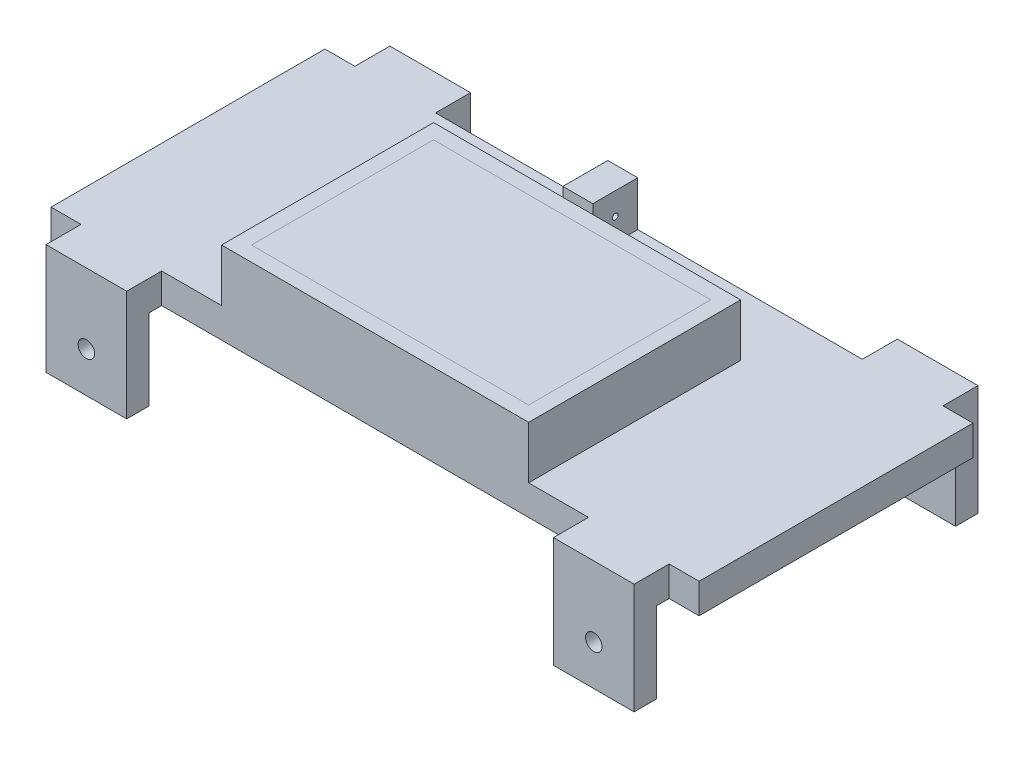
SolidWorks part; units mm, degrees
ref_plane "Front Plane" through (0, 0, 0) normal (0, 0, 1) x (1, 0, 0)
ref_plane "Top Plane" through (0, 0, 0) normal (0, 1, 0) x (1, 0, 0)
ref_plane "Right Plane" through (0, 0, 0) normal (1, 0, 0) x (0, 0, -1)
sketch "Sketch1" plane through (0, 0, 0) normal (1, 0, 0) x (0, 0, -1)
  line L0 (18.2875, 20.8275) -> (-18.2875, 20.8275)
  line L1 (14.2875, -16.8275) -> (-14.2875, -16.8275)
  line L2 (14.2875, -16.8275) -> (14.2875, 16.8275)
  line L3 (14.2875, 16.8275) -> (-14.2875, 16.8275)
  line L4 (-14.2875, -16.8275) -> (-14.2875, 16.8275)
  line L5 (14.2875, -16.8275) -> (-14.2875, 16.8275) construction
  line L6 (14.2875, 16.8275) -> (-14.2875, -16.8275) construction
  line L7 (-18.2875, -20.8275) -> (-18.2875, 20.8275)
  line L8 (18.2875, -20.8275) -> (-18.2875, -20.8275)
  line L9 (18.2875, -20.8275) -> (18.2875, 20.8275)
  point P0 (0, 0)
  dimension "D1" = 28.575
  dimension "D2" = 33.655
  dimension "D3" = 4
extrude "Boss-Extrude1" add sketch "Sketch1" along normal mid plane 82.55
sketch "Sketch2" plane through (-41.275, 0, 0) normal (-1, 0, 0) x (0, 0, 1)
  line L4 (-18.2875, 20.8275) -> (-18.2875, -20.8275)
  line L5 (-18.2875, -20.8275) -> (18.2875, -20.8275)
  line L6 (18.2875, -20.8275) -> (18.2875, 20.8275)
  line L7 (18.2875, 20.8275) -> (-18.2875, 20.8275)
  line L8 (-18.2875, 20.8275) -> (-18.2875, -20.8275)
  line L9 (-18.2875, -20.8275) -> (18.2875, -20.8275)
  line L10 (18.2875, -20.8275) -> (18.2875, 20.8275)
  line L11 (18.2875, 20.8275) -> (-18.2875, 20.8275)
  dimension "D1" = 0
extrude "Boss-Extrude2" add sketch "Sketch2" along normal blind 2
mirror "Mirror1" about plane through (0, 0, 0) normal (1, 0, 0) of "Boss-Extrude2"
sketch "Sketch4" plane through (0, -20.8275, 0) normal (0, -1, 0) x (1, 0, 0)
  line L4 (43.275, 18.2875) -> (-43.275, 18.2875)
  line L5 (-43.275, 18.2875) -> (-43.275, -18.2875)
  line L6 (-43.275, -18.2875) -> (43.275, -18.2875)
  line L7 (43.275, -18.2875) -> (43.275, 18.2875)
  line L8 (43.275, 18.2875) -> (-43.275, 18.2875)
  line L9 (-43.275, 18.2875) -> (-43.275, -18.2875)
  line L10 (-43.275, -18.2875) -> (43.275, -18.2875)
  line L11 (43.275, -18.2875) -> (43.275, 18.2875)
  dimension "D1" = 0
extrude "Cut-Extrude2" cut sketch "Sketch4" against normal blind 37.655
sketch "Sketch5" plane through (0, 0, -18.2875) normal (0, 0, -1) x (-1, 0, 0)
  line L1 (-28.4998, 6.0523) -> (-39.275, 6.0523) construction
  line L2 (-28.4998, 6.0523) -> (-28.4998, 16.8275) construction
  line L3 (-28.4998, 16.8275) -> (-39.275, 16.8275) construction
  line L4 (-39.275, 6.0523) -> (-39.275, 16.8275) construction
  line L5 (-28.4998, 6.0523) -> (-39.275, 16.8275) construction
  line L6 (-28.4998, 16.8275) -> (-39.275, 6.0523) construction
  line L7 (43.275, 16.8275) -> (-43.275, 16.8275) construction
  line L8 (-43.275, 20.8275) -> (-43.275, 16.8275) construction
  line L9 (-39.275, 16.8275) -> (-28.4998, 16.8275)
  line L10 (-31.4998, 9.0523) -> (-36.275, 9.0523) construction
  line L11 (-31.4998, 9.0523) -> (-31.4998, 13.8275) construction
  line L12 (-31.4998, 13.8275) -> (-36.275, 13.8275) construction
  line L13 (-36.275, 9.0523) -> (-36.275, 13.8275) construction
  line L14 (-31.4998, 9.0523) -> (-36.275, 13.8275) construction
  line L15 (-31.4998, 13.8275) -> (-36.275, 9.0523) construction
  line L16 (-28.4998, 16.8275) -> (-28.4998, 20.8275)
  line L17 (-43.275, 20.8275) -> (43.275, 20.8275) construction
  line L18 (-28.4998, 20.8275) -> (-39.275, 20.8275)
  line L19 (-39.275, 20.8275) -> (-39.275, 16.8275)
  point P0 (-33.8874, 11.4399)
  point P9 (-33.8874, 11.4399)
  dimension "D1" = 4
  dimension "D2" = 3
  dimension "D3" = 4.7752
extrude "Boss-Extrude3" add sketch "Sketch5" along normal blind 1.6764
sketch "Sketch6" plane through (0, 0, -19.9639) normal (0, 0, -1) x (-1, 0, 0)
  line L0 (-33.8874, 16.8275) -> (-33.8874, 6.0523) construction
  line L1 (-28.4998, 6.0523) -> (-39.275, 6.0523)
  line L2 (-28.4998, 6.0523) -> (-28.4998, 20.8275)
  line L3 (-28.4998, 20.8275) -> (-39.275, 20.8275)
  line L4 (-39.275, 6.0523) -> (-39.275, 20.8275)
  line L5 (-28.4998, 6.0523) -> (-39.275, 20.8275) construction
  line L6 (-28.4998, 20.8275) -> (-39.275, 6.0523) construction
  line L7 (-39.275, 16.8275) -> (-28.4998, 16.8275) construction
  circle A0 centre (-33.8874, 11.4399) radius 1.1
  point P0 (-33.8874, 13.4399)
  dimension "D1" = 2.2
extrude "Boss-Extrude4" add sketch "Sketch6" along normal blind 3
mirror "Mirror2" about plane through (0, 0, 0) normal (1, 0, 0) of "Boss-Extrude4", "Boss-Extrude3"
mirror "Mirror3" about plane through (0, 0, 0) normal (0, 0, 1) of "Boss-Extrude3", "Mirror2", "Boss-Extrude4"
sketch "Sketch7" plane through (0, 20.8275, 0) normal (0, 1, 0) x (1, 0, 0)
  line L0 (-5.495, 18.2875) -> (-5.495, 12.2875)
  line L1 (28.4998, 18.2875) -> (-28.4998, 18.2875) construction
  line L2 (-5.495, 12.2875) -> (-1.495, 12.2875)
  line L3 (-1.495, 12.2875) -> (-1.495, 18.2875)
  line L4 (-1.495, 18.2875) -> (-5.495, 18.2875)
  line L5 (-43.275, -18.2875) -> (-43.275, 18.2875) construction
  dimension "D1" = 37.78
  dimension "D2" = 4
  dimension "D3" = 6
extrude "Boss-Extrude5" add sketch "Sketch7" along normal blind 6
sketch "Sketch8" plane through (-1.495, 0, 0) normal (1, 0, 0) x (0, 0, -1)
  line L0 (12.2875, 23.8275) -> (18.2875, 23.8275) construction
  line L1 (12.2875, 26.8275) -> (12.2875, 20.8275) construction
  line L2 (18.2875, 26.8275) -> (18.2875, 20.8275) construction
  circle A0 centre (15.2875, 23.8275) radius 0.381
  dimension "D1" = 0.762
extrude "Cut-Extrude3" cut sketch "Sketch8" against normal through all
sketch "Sketch9" plane through (0, 20.8275, 0) normal (0, 1, 0) x (1, 0, 0)
  line L0 (28.4998, -18.2875) -> (-28.4998, -18.2875) construction
  line L1 (20.51, -18.2875) -> (-20.51, -18.2875)
  line L2 (20.51, -18.2875) -> (20.51, 10.0325)
  line L3 (20.51, 10.0325) -> (-20.51, 10.0325)
  line L4 (-20.51, -18.2875) -> (-20.51, 10.0325)
  line L5 (20.51, -18.2875) -> (-20.51, 10.0325) construction
  line L6 (20.51, 10.0325) -> (-20.51, -18.2875) construction
  line L7 (16.51, -14.2875) -> (-16.51, -14.2875)
  line L8 (16.51, -14.2875) -> (16.51, 6.0325)
  line L9 (16.51, 6.0325) -> (-16.51, 6.0325)
  line L10 (-16.51, -14.2875) -> (-16.51, 6.0325)
  line L11 (16.51, -14.2875) -> (-16.51, 6.0325) construction
  line L12 (16.51, 6.0325) -> (-16.51, -14.2875) construction
  line L13 (0, -4.1275) -> (0, -18.2875) construction
  point P0 (0, -4.1275)
  point P5 (0, -4.1275)
  dimension "D1" = 33.02
  dimension "D2" = 20.32
  dimension "D3" = 4
  dimension "D4" = 4
extrude "Boss-Extrude6" add sketch "Sketch9" along normal blind 3
sketch "Sketch10" plane through (0, 23.8275, 0) normal (0, 1, 0) x (1, 0, 0)
  line L0 (18.51, 8.0325) -> (-18.51, 8.0325)
  line L1 (-18.51, 8.0325) -> (-18.51, -16.2875)
  line L2 (-18.51, -16.2875) -> (18.51, -16.2875)
  line L3 (18.51, -16.2875) -> (18.51, 8.0325)
  line L4 (-20.51, 10.0325) -> (-20.51, -18.2875)
  line L5 (-20.51, -18.2875) -> (20.51, -18.2875)
  line L6 (20.51, -18.2875) -> (20.51, 10.0325)
  line L7 (20.51, 10.0325) -> (-20.51, 10.0325)
  line L8 (-20.51, 10.0325) -> (-20.51, -18.2875)
  line L9 (-20.51, -18.2875) -> (20.51, -18.2875)
  line L10 (20.51, -18.2875) -> (20.51, 10.0325)
  line L11 (20.51, 10.0325) -> (-20.51, 10.0325)
  dimension "D1" = 0
  dimension "D2" = 2
extrude "Boss-Extrude7" add sketch "Sketch10" along normal blind 4
sketch "Sketch11" plane through (0, 23.8275, 0) normal (0, 1, 0) x (1, 0, 0)
  line L4 (18.51, -16.2875) -> (18.51, 8.0325)
  line L5 (18.51, 8.0325) -> (-18.51, 8.0325)
  line L6 (-18.51, 8.0325) -> (-18.51, -16.2875)
  line L7 (-18.51, -16.2875) -> (18.51, -16.2875)
  line L8 (18.51, -16.2875) -> (18.51, 8.0325)
  line L9 (18.51, 8.0325) -> (-18.51, 8.0325)
  line L10 (-18.51, 8.0325) -> (-18.51, -16.2875)
  line L11 (-18.51, -16.2875) -> (18.51, -16.2875)
  dimension "D1" = 0
extrude "Boss-Extrude8" add sketch "Sketch11" along normal blind 4 separate body
